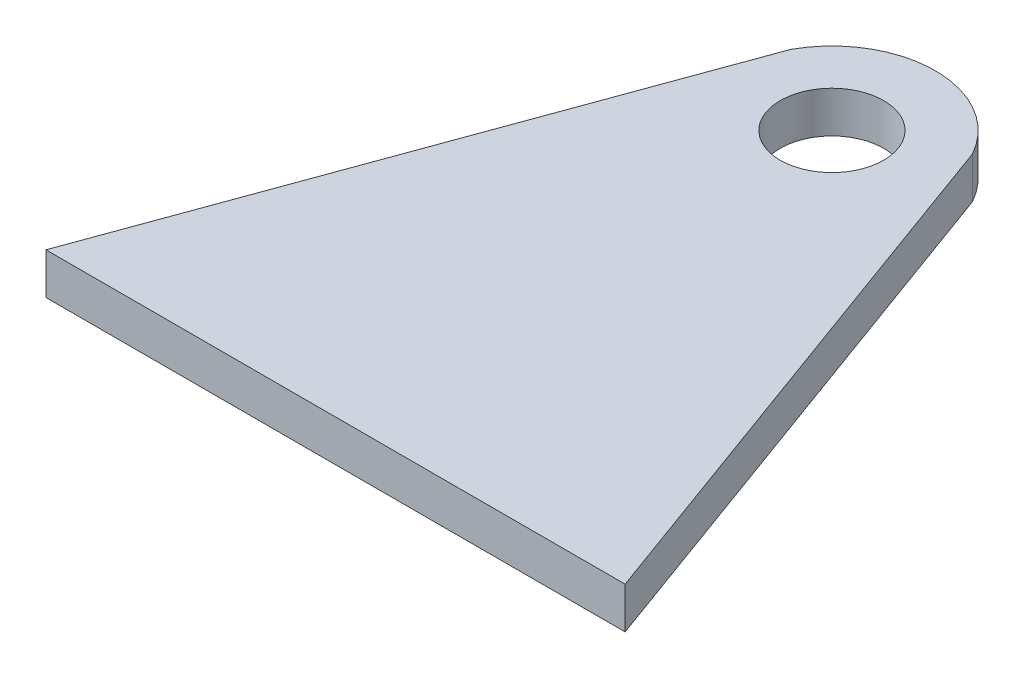
SolidWorks part; units mm, degrees
ref_plane "Front Plane" through (0, 0, 0) normal (0, 0, 1) x (1, 0, 0)
ref_plane "Top Plane" through (0, 0, 0) normal (0, 1, 0) x (1, 0, 0)
ref_plane "Right Plane" through (0, 0, 0) normal (1, 0, 0) x (0, 0, -1)
sketch "Sketch9" plane through (0, 0, 0) normal (0, 1, 0) x (1, 0, 0)
  line L1 (0, -240) -> (140, -240)
  line L2 (0, -240) -> (-140, -240)
  line L3 (-140, -240) -> (-43.8941, 23.9439)
  line L4 (140, -240) -> (43.8941, 23.9439)
  circle A0 centre (0, 0) radius 25
  arc A1 (43.8941, 23.9439) -> (-43.8941, 23.9439) centre (0, 0) ccw
  dimension "D1" = 280
  dimension "D2" = 240
  dimension "D3" = 50
  dimension "D4" = 50
extrude "Boss-Extrude7" add sketch "Sketch9" along normal mid plane 20
